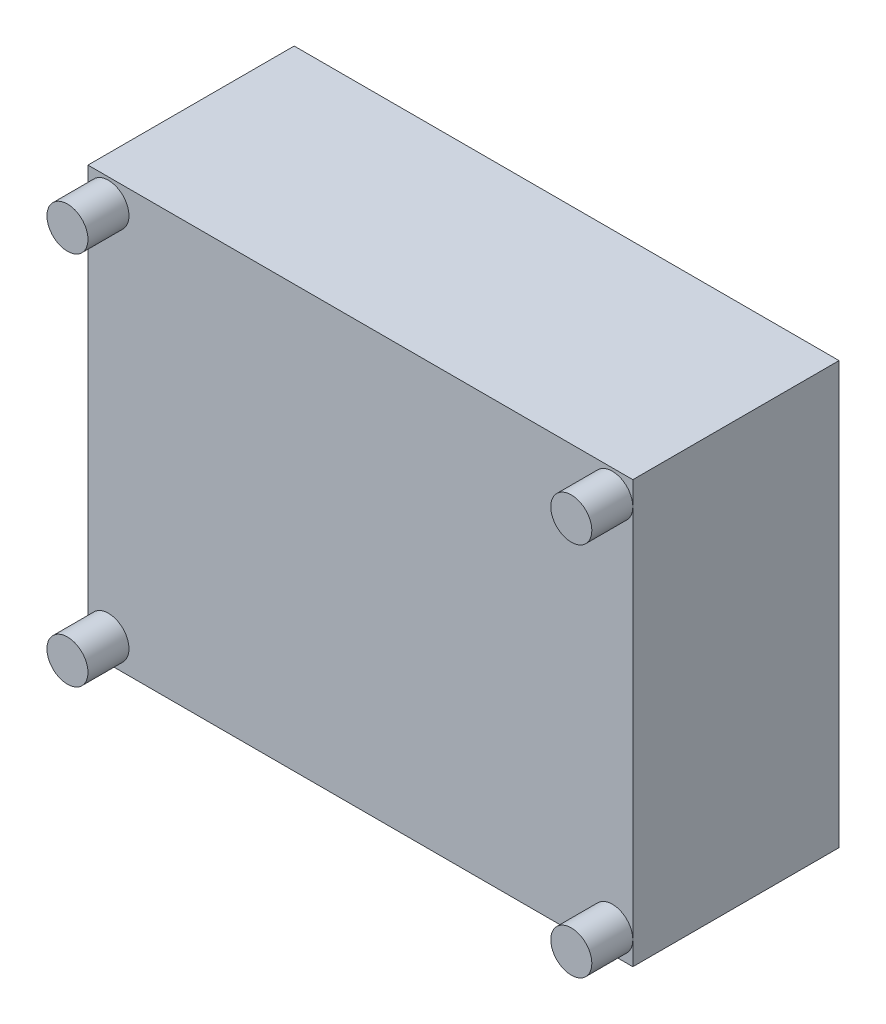
SolidWorks part; units mm, degrees
ref_plane "Plan de face" through (0, 0, 0) normal (0, 0, 1) x (1, 0, 0)
ref_plane "Plan de dessus" through (0, 0, 0) normal (0, 1, 0) x (1, 0, 0)
ref_plane "Plan de droite" through (0, 0, 0) normal (1, 0, 0) x (0, 0, -1)
sketch "Esquisse1" plane through (0, 0, 0) normal (0, 0, 1) x (1, 0, 0)
  line L1 (0, 0) -> (93, 0)
  line L2 (0, 0) -> (0, -72)
  line L3 (0, -72) -> (93, -72)
  line L4 (93, 0) -> (93, -72)
  dimension "D1" = 93
  dimension "D2" = 72
extrude "Boss.-Extru.1" add sketch "Esquisse1" along normal blind 35.2
sketch "Esquisse2" plane through (0, 0, 0) normal (0, 0, -1) x (-1, 0, 0)
  line L0 (-89.5, 0) -> (-89.5, -4) construction
  line L1 (-93, 0) -> (0, 0) construction
  line L2 (-89.5, -68) -> (-89.5, -72) construction
  line L3 (0, -72) -> (-93, -72) construction
  line L4 (-93, -4) -> (-89.5, -4) construction
  line L6 (-93, -72) -> (-93, 0) construction
  line L7 (-3.5, -4) -> (0, -4) construction
  line L8 (0, 0) -> (0, -72) construction
  circle A0 centre (-89.5, -4) radius 1.75
  circle A1 centre (-3.5, -4) radius 1.75
  circle A2 centre (-89.5, -68) radius 1.75
  circle A3 centre (-3.5, -68) radius 1.75
  dimension "D1" = 3.5
  dimension "D2" = 64
  dimension "D3" = 86
extrude "Enlèv. mat.-Extru.1" cut sketch "Esquisse2" against normal through all
sketch "Esquisse3" plane through (0, 0, 35.2) normal (0, 0, 1) x (1, 0, 0)
  line L0 (93, -72) -> (93, 0) construction
  circle A0 centre (89.5, -68) radius 3.5
  circle A1 centre (3.5, -68) radius 3.5
  circle A2 centre (89.5, -4) radius 3.5
  circle A3 centre (3.5, -4) radius 3.5
extrude "Boss.-Extru.2" add sketch "Esquisse3" along normal blind 7
